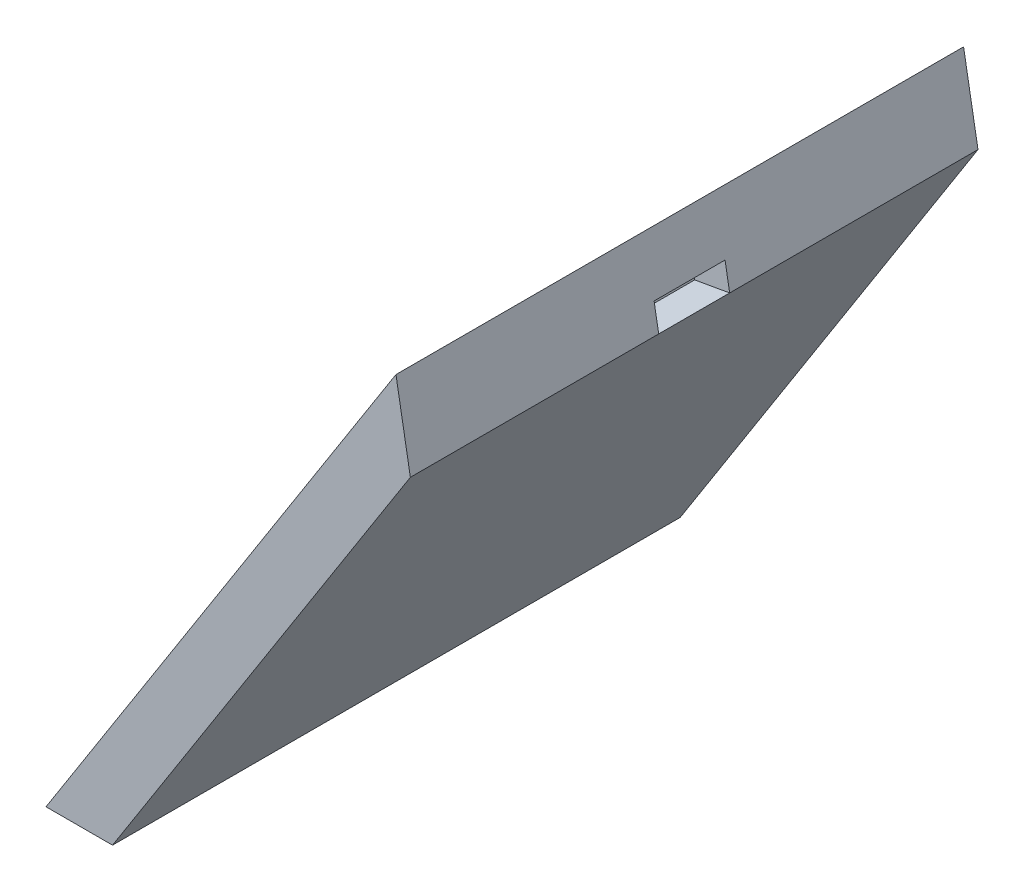
SolidWorks part; units mm, degrees
ref_plane "Front Plane" through (0, 0, 0) normal (0, 0, 1) x (1, 0, 0)
ref_plane "Top Plane" through (0, 0, 0) normal (0, 1, 0) x (1, 0, 0)
ref_plane "Right Plane" through (0, 0, 0) normal (1, 0, 0) x (0, 0, -1)
sketch "Sketch1" plane through (0, 0, 0) normal (0, 0, 1) x (1, 0, 0)
  line L0 (0, 0) -> (7.5, 0)
  line L1 (7.5, 0) -> (41.0812, 52.712)
  line L2 (41.0812, 52.712) -> (39.4562, 61.9338)
  line L3 (39.4562, 61.9338) -> (0, 0)
  dimension "D1" = 73.4342
  dimension "D2" = 7.5
  dimension "D3" = 9.2218
  dimension "D4" = 62.5
extrude "Boss-Extrude1" add sketch "Sketch1" along normal blind 64
sketch "Sketch2" plane through (48.853, 8.6087, 0) normal (0.9848, 0.1735, 0) x (0, 0, -1)
  line L0 (-32, 44.7828) -> (-28, 44.7828)
  line L1 (-64, 44.7828) -> (0, 44.7828) construction
  line L2 (-28, 44.7828) -> (-28, 47.7828)
  line L3 (-28, 47.7828) -> (-36, 47.7828)
  line L4 (-36, 47.7828) -> (-36, 44.7828)
  line L5 (-36, 44.7828) -> (-32, 44.7828)
  dimension "D1" = 3
  dimension "D2" = 4
extrude "Cut-Extrude1" cut sketch "Sketch2" against normal blind 4
